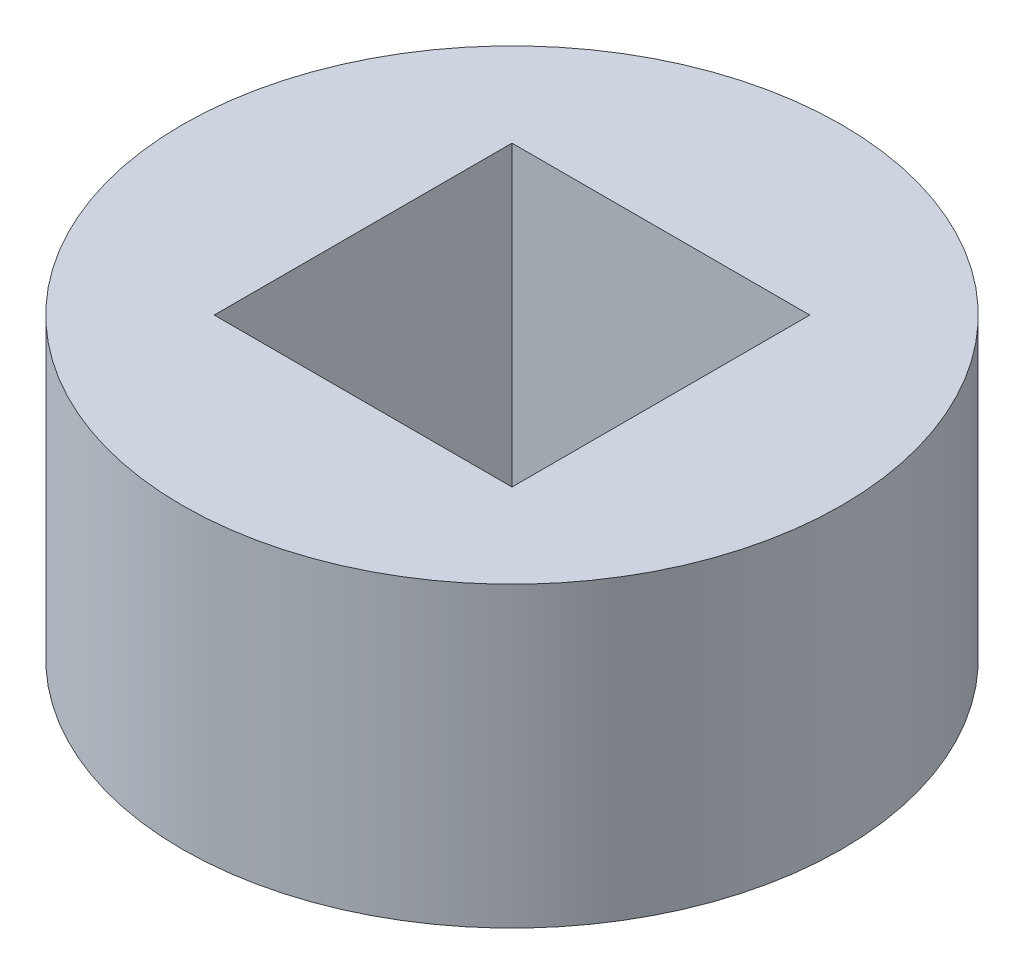
SolidWorks part; units mm, degrees
ref_plane "Front Plane" through (0, 0, 0) normal (0, 0, 1) x (1, 0, 0)
ref_plane "Top Plane" through (0, 0, 0) normal (0, 1, 0) x (1, 0, 0)
ref_plane "Right Plane" through (0, 0, 0) normal (1, 0, 0) x (0, 0, -1)
sketch "Elevator Axle Bearing" plane through (0, 0, 0) normal (0, 1, 0) x (1, 0, 0)
  line L1 (-3.175, 3.175) -> (3.175, 3.175)
  line L2 (-3.175, 3.175) -> (-3.175, -3.175)
  line L3 (-3.175, -3.175) -> (3.175, -3.175)
  line L4 (3.175, 3.175) -> (3.175, -3.175)
  line L5 (-3.175, 3.175) -> (3.175, -3.175) construction
  line L6 (-3.175, -3.175) -> (3.175, 3.175) construction
  circle A0 centre (0, 0) radius 7.0301
  dimension "D1" = 14.0603
  dimension "D2" = 6.35
  dimension "D3" = 6.35
extrude "Boss-Extrude1" add sketch "Elevator Axle Bearing" along normal blind 6.35
equation "\"Ball Diameter\"= 1.75in"
equation "\"Sheet Thickness\"= 0.25in"
equation "\"Screw Diameter\"= .17in"
equation "\"Robot Diameter\"= 16in"
equation "\"Castor Screw Diameter\"= 0.22in"
equation "\"Wheel Diameter\" = 4in"
equation "\"Nut Diameter\" = 8.4mm"
equation "\"Nut Height\" = 2.9mm"
equation "\"Screw Height\" = 0.55in"
equation "\"Pulley Diameter\" = 1in"
equation "\"Reactor Height\" = 14in"
equation "\"Elevator Height\" = 11.5in"
equation "\"Elevator Width\" = \"Ball Diameter\" + 0.25in"
equation "\"Elevator Bearing Diameter\" = sqr(2*(\"Sheet Thickness\"^2)) + 0.2in"
equation "\"Elevator Axle Length\" = \"Elevator Width\" + 6*\"Sheet Thickness\""
equation "\"D1@Elevator Axle Bearing\"=\"Elevator Bearing Diameter\""
equation "\"D2@Elevator Axle Bearing\"=\"Sheet Thickness\""
equation "\"D3@Elevator Axle Bearing\"=\"Sheet Thickness\""
equation "\"D1@Boss-Extrude1\"=\"Sheet Thickness\""
